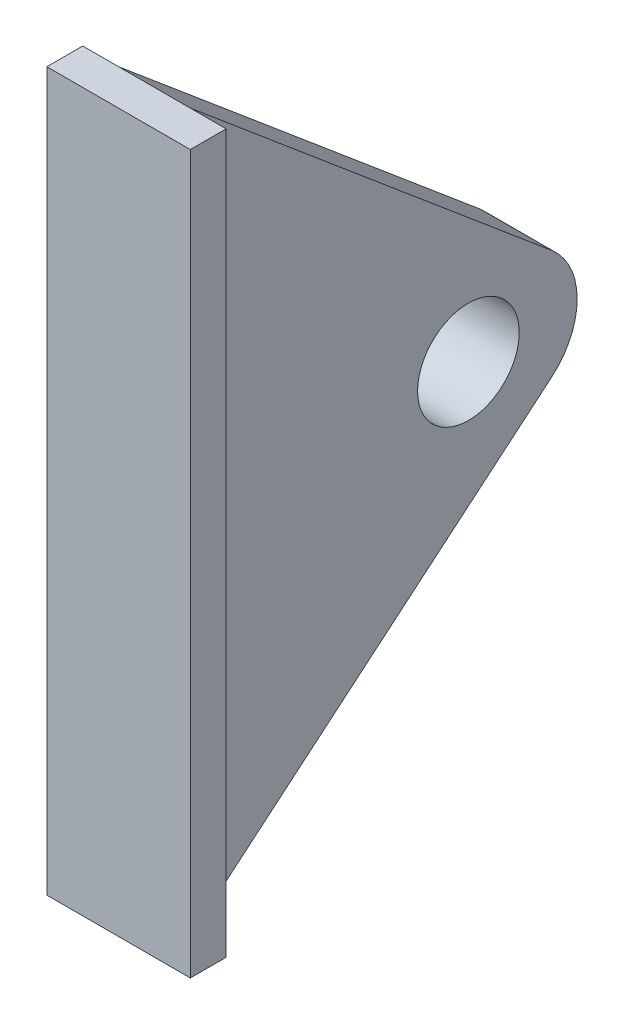
SolidWorks part; units mm, degrees
ref_plane "前视基准面" through (0, 0, 0) normal (0, 0, 1) x (1, 0, 0)
ref_plane "上视基准面" through (0, 0, 0) normal (0, 1, 0) x (1, 0, 0)
ref_plane "右视基准面" through (0, 0, 0) normal (1, 0, 0) x (0, 0, -1)
sketch "草图1" plane through (0, 0, 0) normal (0, 0, 1) x (1, 0, 0)
  line L1 (6, 30) -> (-6, 30)
  line L2 (6, 30) -> (6, -30)
  line L3 (6, -30) -> (-6, -30)
  line L4 (-6, 30) -> (-6, -30)
  line L5 (6, 30) -> (-6, -30) construction
  line L6 (6, -30) -> (-6, 30) construction
  point P0 (0, 0)
  dimension "D1" = 12
  dimension "D2" = 60
extrude "凸台-拉伸1" add sketch "草图1" along normal blind 3
sketch "草图3" plane through (0, 0, 0) normal (1, 0, 0) x (0, 0, -1)
  line L0 (0, 30) -> (35.6741, 0)
  line L1 (35.6741, 0) -> (0, -30)
  line L2 (0, -30) -> (0, 30)
extrude "凸台-拉伸2" add sketch "草图3" along normal blind 3 and the other way blind 3
fillet "圆角1" radius 6 1 edges at (0, 0, -35.6741)
sketch "草图4" plane through (-3, 0, 0) normal (-1, 0, 0) x (0, 0, 1)
  circle A0 centre (-23.2572, 0) radius 4.25
  dimension "D1" = 8.5
extrude "切除-拉伸1" cut sketch "草图4" against normal through all
